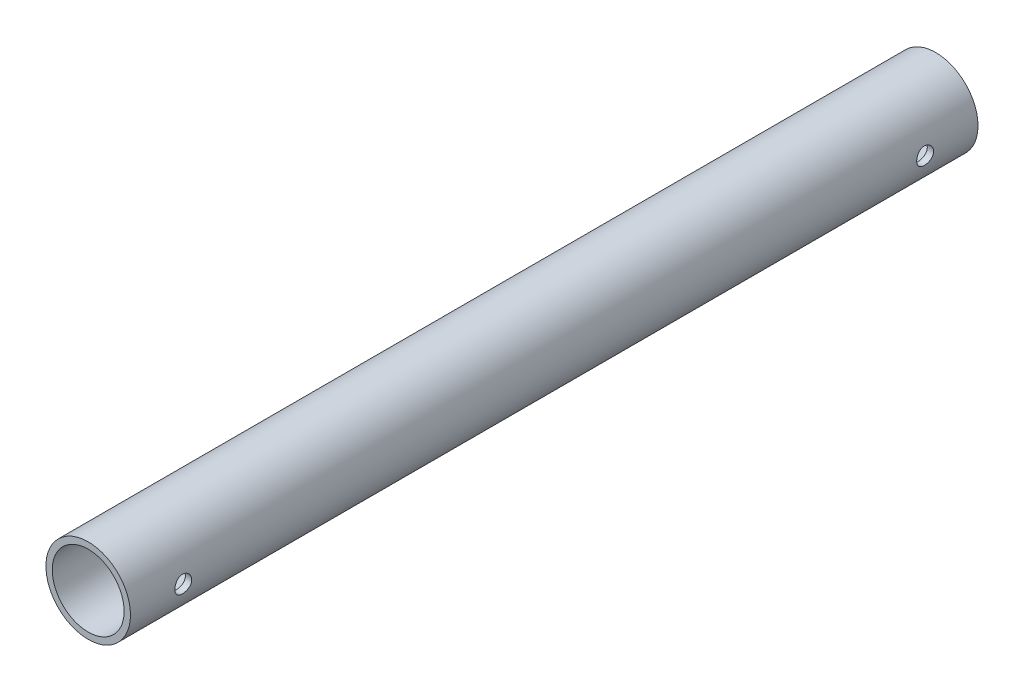
SolidWorks part; units mm, degrees
ref_plane "Front Plane" through (0, 0, 0) normal (0, 0, 1) x (1, 0, 0)
ref_plane "Top Plane" through (0, 0, 0) normal (0, 1, 0) x (1, 0, 0)
ref_plane "Right Plane" through (0, 0, 0) normal (1, 0, 0) x (0, 0, -1)
sketch "Sketch1" plane through (0, 0, 0) normal (0, 0, 1) x (1, 0, 0)
  circle A0 centre (0, 0) radius 10
  circle A1 centre (0, 0) radius 8.5
  dimension "D1" = 20
  dimension "D2" = 1.5
extrude "Boss-Extrude1" add sketch "Sketch1" along normal blind 100.25
sketch "Sketch2" plane through (0, 0, 0) normal (1, 0, 0) x (0, 0, -1)
  line L0 (-100.25, 10) -> (-100.25, -10) construction
  circle A0 centre (-87.75, 0) radius 2
  dimension "D1" = 4
  dimension "D2" = 12.5
extrude "Cut-Extrude1" cut sketch "Sketch2" against normal through all both and the other way through all
mirror "Mirror1" about plane through (0, 0, 0) normal (0, 0, 1) of "Cut-Extrude1", "Boss-Extrude1"
